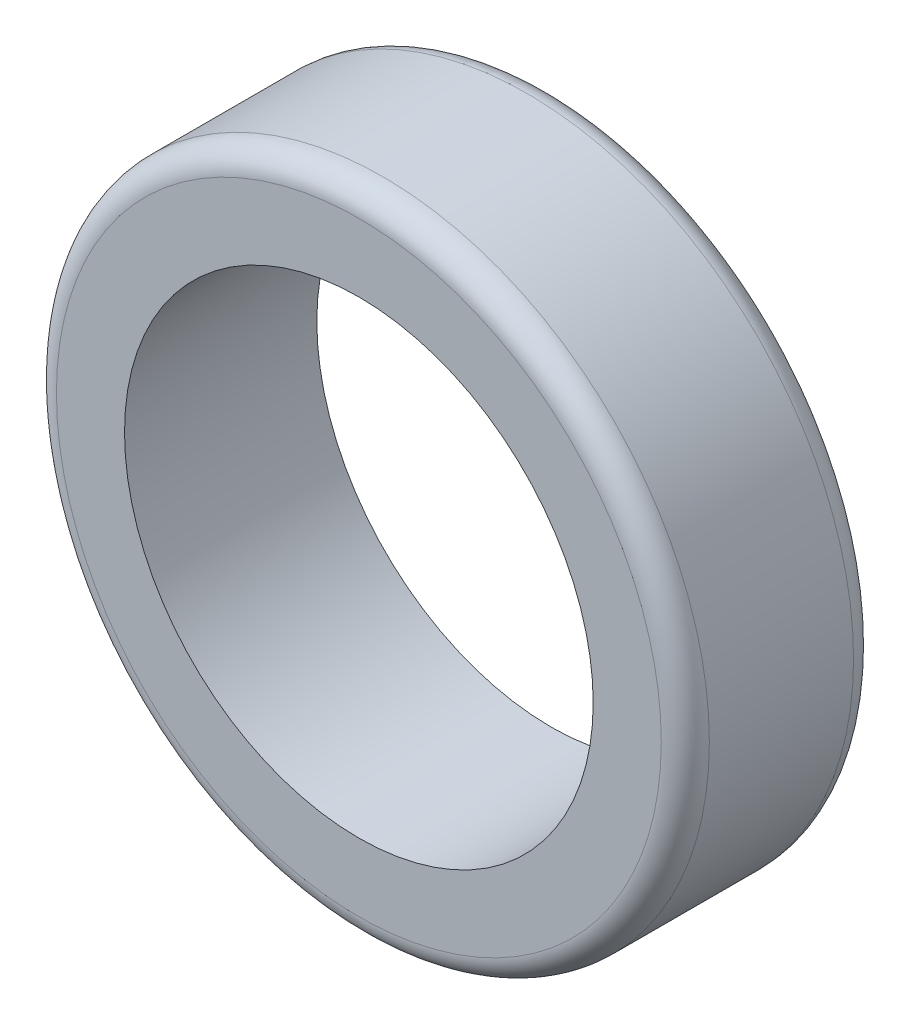
SolidWorks part; units mm, degrees
ref_plane "Front Plane" through (0, 0, 0) normal (0, 0, 1) x (1, 0, 0)
ref_plane "Top Plane" through (0, 0, 0) normal (0, 1, 0) x (1, 0, 0)
ref_plane "Right Plane" through (0, 0, 0) normal (1, 0, 0) x (0, 0, -1)
sketch "Sketch1" plane through (0, 0, 0) normal (0, 0, 1) x (1, 0, 0)
  circle A0 centre (0, 0) radius 12.3825
  circle A1 centre (0, 0) radius 17.25
  dimension "D1" = 24.765
  dimension "D2" = 34.5
extrude "Boss-Extrude1" add sketch "Sketch1" along normal blind 10.16
fillet "Fillet1" radius 1.27 2 edges at (17.25, 0, 0) (17.25, 0, 10.16)
